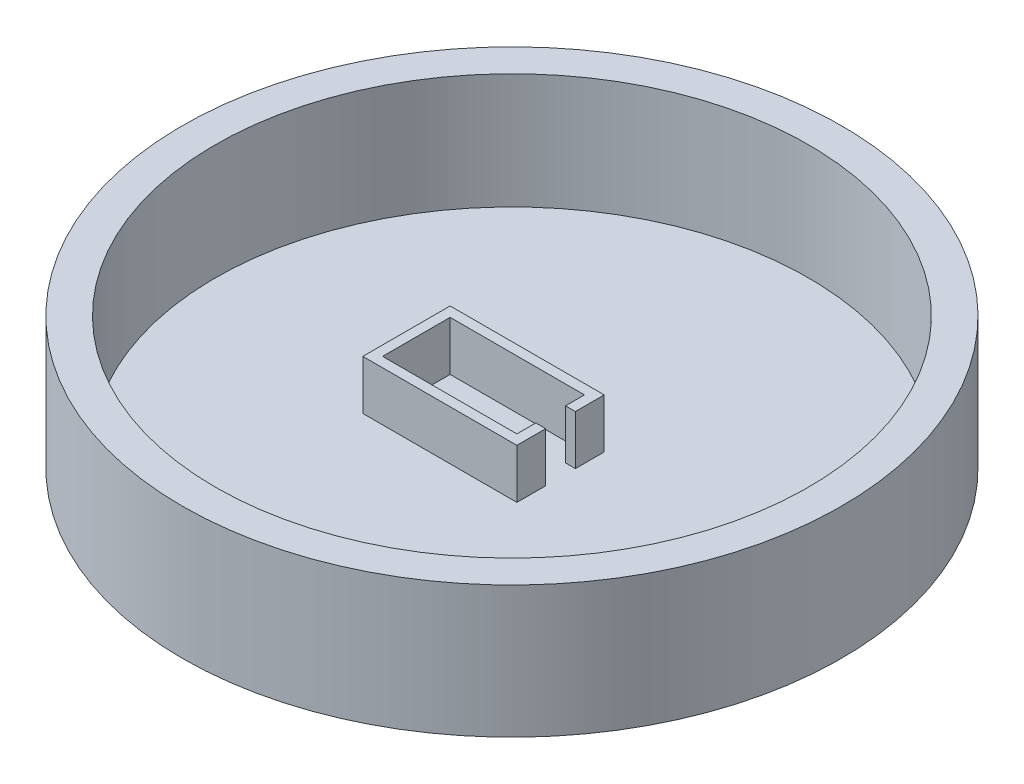
SolidWorks part; units mm, degrees
ref_plane "Front Plane" through (0, 0, 0) normal (0, 0, 1) x (1, 0, 0)
ref_plane "Top Plane" through (0, 0, 0) normal (0, 1, 0) x (1, 0, 0)
ref_plane "Right Plane" through (0, 0, 0) normal (1, 0, 0) x (0, 0, -1)
sketch "Sketch1" plane through (0, 0, 0) normal (0, 1, 0) x (1, 0, 0)
  circle A0 centre (0, 0) radius 100
  dimension "D1" = 200
extrude "Boss-Extrude1" add sketch "Sketch1" along normal blind 40
sketch "Sketch2" plane through (0, 40, 0) normal (0, 1, 0) x (1, 0, 0)
  circle A0 centre (0, 0) radius 90
  dimension "D1" = 180
extrude "Cut-Extrude1" cut sketch "Sketch2" against normal blind 35
sketch "Sketch3" plane through (0, 5, 0) normal (0, 1, 0) x (1, 0, 0)
  line L0 (0, -10.25) -> (0, 10.25) construction
  line L1 (0, 10.25) -> (11.75, 10.25)
  line L2 (11.75, 10.25) -> (11.75, -10.25)
  line L3 (11.75, -10.25) -> (0, -10.25)
  line L4 (0, -10.25) -> (-29, -10.25)
  line L5 (-29, -10.25) -> (-29, 10.25)
  line L6 (-29, 10.25) -> (0, 10.25)
  line L7 (14.75, 13.25) -> (14.75, -13.25)
  line L8 (14.75, -13.25) -> (-32, -13.25)
  line L9 (-32, -13.25) -> (-32, 13.25)
  line L10 (-32, 13.25) -> (14.75, 13.25)
  point P3 (0, 0)
  dimension "D1" = 20.5
  dimension "D2" = 11.75
  dimension "D3" = 29
  dimension "D4" = 3
  dimension "D5" = 3
  dimension "D6" = 3
  dimension "D7" = 3
extrude "Boss-Extrude2" add sketch "Sketch3" along normal blind 15
sketch "Sketch4" plane through (0, 20, 0) normal (0, 1, 0) x (1, 0, 0)
  line L0 (11.75, 4.5) -> (14.75, 4.5)
  line L1 (11.75, -10.25) -> (11.75, 10.25) construction
  line L2 (14.75, -13.25) -> (14.75, 13.25) construction
  line L3 (14.75, 4.5) -> (14.75, -4.5)
  line L4 (14.75, -13.25) -> (14.75, 13.25) construction
  line L5 (14.75, -4.5) -> (11.75, -4.5)
  line L6 (11.75, -4.5) -> (11.75, 4.5)
  point P6 (14.75, 0)
  point P11 (14.75, 0)
  dimension "D1" = 9
extrude "Cut-Extrude2" cut sketch "Sketch4" against normal blind 15
